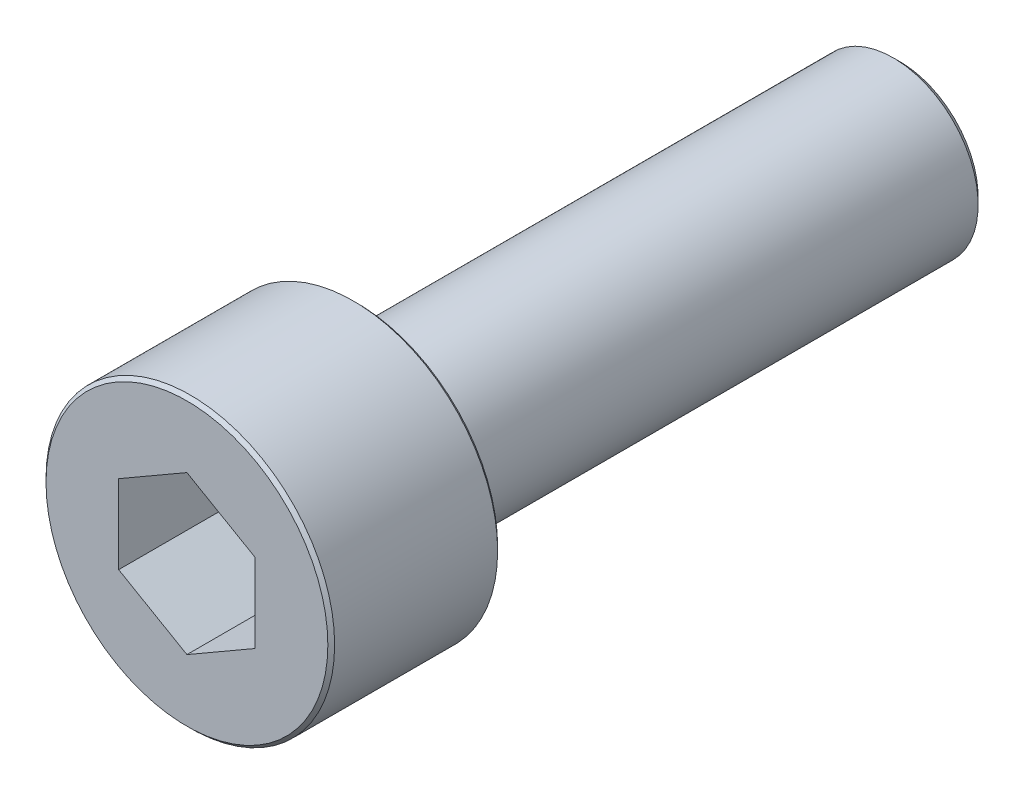
SolidWorks part; units mm, degrees
ref_plane "前视基准面" through (0, 0, 0) normal (0, 0, 1) x (1, 0, 0)
ref_plane "上视基准面" through (0, 0, 0) normal (0, 1, 0) x (1, 0, 0)
ref_plane "右视基准面" through (0, 0, 0) normal (1, 0, 0) x (0, 0, -1)
other "Configuration Table"
sketch "草图1" plane through (0, 0, 0) normal (0, 1, 0) x (1, 0, 0)
  line L0 (4.25, -16) -> (0, -16)
  line L1 (0, -16) -> (0, -21)
  line L2 (0, -21) -> (4.25, -21)
  line L3 (4.25, -21) -> (4.25, -16)
  line L4 (0, -16) -> (0, -21) construction
revolve "旋转1" add sketch "草图1" angle 360 about L4
sketch "草图2" plane through (0, 0, 16) normal (0, 0, -1) x (-1, 0, 0)
  circle A0 centre (0, 0) radius 2.5
extrude "凸台-拉伸1" add sketch "草图2" along normal blind 16
sketch "草图3" plane through (0, 0, 21) normal (0, 0, 1) x (1, 0, 0)
  line L0 (-2.01, -1.1605) -> (0, -2.3209)
  line L1 (0, -2.3209) -> (2.01, -1.1605)
  line L2 (2.01, -1.1605) -> (2.01, 1.1605)
  line L3 (2.01, 1.1605) -> (0, 2.3209)
  line L4 (0, 2.3209) -> (-2.01, 1.1605)
  line L5 (-2.01, 1.1605) -> (-2.01, -1.1605)
extrude "切除-拉伸1" cut sketch "草图3" against normal blind 3.75
chamfer "倒角1" distance 0.1 angle 45 2 edges at (4.25, 0, 16) (4.25, 0, 21)
chamfer "倒角2" distance 0.2 angle 45 1 edges at (-2.5, 0, 0)
